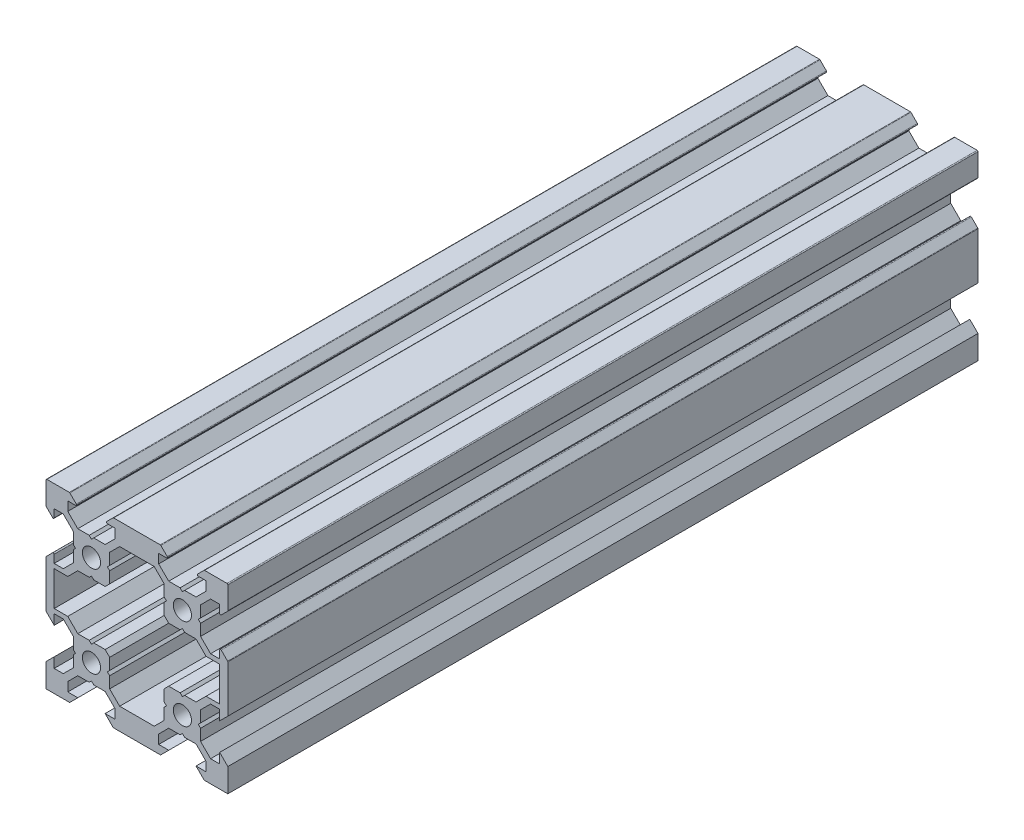
SolidWorks part; units mm, degrees
ref_plane "Front Plane" through (0, 0, 0) normal (0, 0, 1) x (1, 0, 0)
ref_plane "Top Plane" through (0, 0, 0) normal (0, 1, 0) x (1, 0, 0)
ref_plane "Right Plane" through (0, 0, 0) normal (1, 0, 0) x (0, 0, -1)
sketch "Sketch2" plane through (0, 0, 0) normal (0, 0, 1) x (1, 0, 0)
  line L160 (-6.4559, 12.7994) -> (-4.2559, 14.9994)
  line L161 (-4.2559, 14.9994) -> (3.3441, 14.9994)
  line L162 (3.3441, 14.9994) -> (5.5441, 12.7994)
  line L163 (5.5441, 12.7994) -> (5.5441, 10.2894)
  line L164 (5.5441, 10.2894) -> (6.0441, 9.7894)
  line L165 (6.0441, 9.7894) -> (5.5441, 9.2894)
  line L166 (5.5441, 9.2894) -> (5.5441, 6.7793)
  line L167 (5.5441, 6.7793) -> (6.5341, 5.7894)
  line L168 (6.5341, 5.7894) -> (9.0441, 5.7894)
  line L169 (9.0441, 5.7894) -> (9.5441, 6.2894)
  line L170 (9.5441, 6.2894) -> (10.0441, 5.7894)
  line L171 (10.0441, 5.7894) -> (12.5542, 5.7894)
  line L172 (12.5542, 5.7894) -> (14.7542, 3.5894)
  line L173 (14.7542, 3.5894) -> (17.7441, 3.5894)
  line L174 (17.7441, 3.5894) -> (17.7441, -4.0106)
  line L175 (17.7441, -4.0106) -> (14.7542, -4.0106)
  line L176 (14.7542, -4.0106) -> (12.5542, -6.2106)
  line L177 (12.5542, -6.2106) -> (10.0441, -6.2106)
  line L178 (9.5441, -6.7106) -> (10.0441, -6.2106)
  line L179 (9.0441, -6.2106) -> (9.5441, -6.7106)
  line L180 (9.0441, -6.2106) -> (6.5341, -6.2106)
  line L181 (6.5341, -6.2106) -> (5.5441, -7.2006)
  line L182 (5.5441, -7.2006) -> (5.5441, -9.7106)
  line L183 (6.0441, -10.2106) -> (5.5441, -9.7106)
  line L184 (5.5441, -10.7106) -> (6.0441, -10.2106)
  line L185 (5.5441, -10.7106) -> (5.5441, -13.2207)
  line L186 (5.5441, -13.2207) -> (3.3441, -15.4207)
  line L187 (3.3441, -15.4207) -> (-4.2559, -15.4207)
  line L188 (-4.2559, -15.4207) -> (-6.4559, -13.2207)
  line L189 (-6.4559, -13.2207) -> (-6.4559, -10.7106)
  line L190 (-6.9559, -10.2106) -> (-6.4559, -10.7106)
  line L191 (-6.4559, -9.7106) -> (-6.9559, -10.2106)
  line L192 (-6.4559, -9.7106) -> (-6.4559, -7.2006)
  line L193 (-6.4559, -7.2006) -> (-7.4458, -6.2106)
  line L194 (-7.4458, -6.2106) -> (-9.9559, -6.2106)
  line L195 (-10.4559, -6.7106) -> (-9.9559, -6.2106)
  line L196 (-10.9559, -6.2106) -> (-10.4559, -6.7106)
  line L197 (-10.9559, -6.2106) -> (-13.4659, -6.2106)
  line L198 (-13.4659, -6.2106) -> (-15.6659, -4.0106)
  line L199 (-15.6659, -4.0106) -> (-18.6559, -4.0106)
  line L200 (-18.6559, -4.0106) -> (-18.6559, 3.5894)
  line L201 (-18.6559, 3.5894) -> (-15.6659, 3.5894)
  line L202 (-15.6659, 3.5894) -> (-13.4659, 5.7894)
  line L203 (-13.4659, 5.7894) -> (-10.9559, 5.7894)
  line L204 (-10.9559, 5.7894) -> (-10.4559, 6.2894)
  line L205 (-10.4559, 6.2894) -> (-9.9559, 5.7894)
  line L206 (-9.9559, 5.7894) -> (-7.4458, 5.7894)
  line L207 (-7.4458, 5.7894) -> (-6.4559, 6.7793)
  line L208 (-6.4559, 9.2894) -> (-6.9559, 9.7894)
  line L209 (-6.9559, 9.7894) -> (-6.4559, 10.2894)
  line L210 (-6.4559, 6.7793) -> (-6.4559, 9.2894)
  line L211 (-6.4559, 10.2894) -> (-6.4559, 12.7994)
  line L212 (-5.2458, -16.4106) -> (-5.2458, -18.4106)
  line L213 (-5.2458, -18.4106) -> (-7.4559, -18.4106)
  line L214 (-7.4559, -18.4106) -> (-5.6559, -20.2106)
  line L215 (-5.6559, -20.2106) -> (4.7441, -20.2106)
  line L216 (4.7441, -20.2106) -> (6.5441, -18.4106)
  line L217 (6.5441, -18.4106) -> (4.3341, -18.4106)
  line L218 (4.3341, -18.4106) -> (4.3341, -16.4106)
  line L219 (4.3341, -16.4106) -> (6.5341, -14.2106)
  line L220 (6.5341, -14.2106) -> (9.0441, -14.2106)
  line L221 (9.0441, -14.2106) -> (9.5441, -13.7106)
  line L222 (9.5441, -13.7106) -> (10.0441, -14.2106)
  line L223 (10.0441, -14.2106) -> (12.5542, -14.2106)
  line L224 (12.5542, -14.2106) -> (14.7542, -16.4106)
  line L225 (14.7542, -16.4106) -> (14.7542, -18.4106)
  line L226 (14.7542, -18.4106) -> (12.5441, -18.4106)
  line L227 (12.5441, -18.4106) -> (14.3441, -20.2106)
  line L228 (14.3441, -20.2106) -> (19.5441, -20.2106)
  line L229 (19.5441, -20.2106) -> (19.5441, -15.0106)
  line L230 (19.5441, -15.0106) -> (17.7441, -13.2106)
  line L231 (17.7441, -13.2106) -> (17.7441, -15.4207)
  line L232 (17.7441, -15.4207) -> (15.7441, -15.4207)
  line L233 (15.7441, -15.4207) -> (13.5441, -13.2207)
  line L234 (13.5441, -13.2207) -> (13.5441, -10.7106)
  line L235 (13.5441, -10.7106) -> (13.0441, -10.2106)
  line L236 (13.0441, -10.2106) -> (13.5441, -9.7106)
  line L237 (13.5441, -9.7106) -> (13.5441, -7.2006)
  line L238 (13.5441, -7.2006) -> (15.7441, -5.0006)
  line L239 (15.7441, -5.0006) -> (17.7441, -5.0006)
  line L240 (17.7441, -5.0006) -> (17.7441, -7.2106)
  line L241 (17.7441, -7.2106) -> (19.5441, -5.4106)
  line L242 (19.5441, -5.4106) -> (19.5441, 4.9066)
  line L243 (19.4856, 5.048) -> (18.0856, 6.448)
  line L244 (17.7441, 6.3066) -> (17.7441, 4.5793)
  line L245 (17.7441, 4.5793) -> (15.7441, 4.5793)
  line L246 (15.7441, 4.5793) -> (13.5441, 6.7793)
  line L247 (13.5441, 6.7793) -> (13.5441, 9.2894)
  line L248 (13.5441, 9.2894) -> (13.0441, 9.7894)
  line L249 (13.0441, 9.7894) -> (13.5441, 10.2894)
  line L250 (13.5441, 10.2894) -> (13.5441, 12.7994)
  line L251 (13.5441, 12.7994) -> (15.7441, 14.9994)
  line L252 (15.7441, 14.9994) -> (17.7441, 14.9994)
  line L253 (17.7441, 14.9994) -> (17.7441, 13.2722)
  line L254 (18.0856, 13.1308) -> (19.4856, 14.5308)
  line L255 (19.5441, 14.6722) -> (19.5441, 19.5894)
  line L256 (19.3441, 19.7894) -> (14.427, 19.7894)
  line L257 (14.2856, 19.7308) -> (12.8856, 18.3308)
  line L258 (13.027, 17.9894) -> (14.7542, 17.9894)
  line L259 (14.7542, 17.9894) -> (14.7542, 15.9894)
  line L260 (14.7542, 15.9894) -> (12.5542, 13.7894)
  line L261 (12.5542, 13.7894) -> (10.0441, 13.7894)
  line L262 (10.0441, 13.7894) -> (9.5441, 13.2894)
  line L263 (9.5441, 13.2894) -> (9.0441, 13.7894)
  line L264 (9.0441, 13.7894) -> (6.5341, 13.7894)
  line L265 (6.5341, 13.7894) -> (4.3341, 15.9894)
  line L266 (4.3341, 15.9894) -> (4.3341, 17.9894)
  line L267 (4.3341, 17.9894) -> (6.0613, 17.9894)
  line L268 (6.2027, 18.3308) -> (4.8027, 19.7308)
  line L269 (4.6613, 19.7894) -> (-5.573, 19.7894)
  line L270 (-5.7144, 19.7308) -> (-7.1144, 18.3308)
  line L271 (-6.973, 17.9894) -> (-5.2458, 17.9894)
  line L272 (-5.2458, 17.9894) -> (-5.2458, 15.9894)
  line L273 (-5.2458, 15.9894) -> (-7.4458, 13.7894)
  line L274 (-7.4458, 13.7894) -> (-9.9559, 13.7894)
  line L275 (-9.9559, 13.7894) -> (-10.4559, 13.2894)
  line L276 (-10.4559, 13.2894) -> (-10.9559, 13.7894)
  line L277 (-10.9559, 13.7894) -> (-13.4659, 13.7894)
  line L278 (-13.4659, 13.7894) -> (-15.6659, 15.9894)
  line L279 (-15.6659, 15.9894) -> (-15.6659, 17.9894)
  line L280 (-15.6659, 17.9894) -> (-13.9387, 17.9894)
  line L281 (-13.7973, 18.3308) -> (-15.1973, 19.7308)
  line L282 (-15.3387, 19.7894) -> (-20.2559, 19.7894)
  line L283 (-20.4559, 19.5894) -> (-20.4559, 14.6722)
  line L284 (-20.3973, 14.5308) -> (-18.9973, 13.1308)
  line L285 (-18.6559, 13.2722) -> (-18.6559, 14.9994)
  line L286 (-18.6559, 14.9994) -> (-16.6559, 14.9994)
  line L287 (-16.6559, 14.9994) -> (-14.4559, 12.7994)
  line L288 (-14.4559, 12.7994) -> (-14.4559, 10.2894)
  line L289 (-14.4559, 10.2894) -> (-13.9559, 9.7894)
  line L290 (-13.9559, 9.7894) -> (-14.4559, 9.2894)
  line L291 (-14.4559, 9.2894) -> (-14.4559, 6.7793)
  line L292 (-14.4559, 6.7793) -> (-16.6559, 4.5793)
  line L293 (-16.6559, 4.5793) -> (-18.6559, 4.5793)
  line L294 (-18.6559, 4.5793) -> (-18.6559, 6.3066)
  line L295 (-18.9973, 6.448) -> (-20.3973, 5.048)
  line L296 (-20.4559, 4.9066) -> (-20.4559, -5.4106)
  line L297 (-20.4559, -5.4106) -> (-18.6559, -7.2106)
  line L298 (-18.6559, -7.2106) -> (-18.6559, -5.0006)
  line L299 (-18.6559, -5.0006) -> (-16.6559, -5.0006)
  line L300 (-16.6559, -5.0006) -> (-14.4559, -7.2006)
  line L301 (-14.4559, -7.2006) -> (-14.4559, -9.7106)
  line L302 (-14.4559, -9.7106) -> (-13.9559, -10.2106)
  line L303 (-13.9559, -10.2106) -> (-14.4559, -10.7106)
  line L304 (-14.4559, -10.7106) -> (-14.4559, -13.2207)
  line L305 (-14.4559, -13.2207) -> (-16.6559, -15.4207)
  line L306 (-16.6559, -15.4207) -> (-18.6559, -15.4207)
  line L307 (-18.6559, -15.4207) -> (-18.6559, -13.2106)
  line L308 (-18.6559, -13.2106) -> (-20.4559, -15.0106)
  line L309 (-20.4559, -15.0106) -> (-20.4559, -20.2106)
  line L310 (-20.4559, -20.2106) -> (-15.2559, -20.2106)
  line L311 (-15.2559, -20.2106) -> (-13.4559, -18.4106)
  line L312 (-13.4559, -18.4106) -> (-15.6659, -18.4106)
  line L313 (-15.6659, -18.4106) -> (-15.6659, -16.4106)
  line L314 (-15.6659, -16.4106) -> (-13.4659, -14.2106)
  line L315 (-13.4659, -14.2106) -> (-10.9559, -14.2106)
  line L316 (-10.9559, -14.2106) -> (-10.4559, -13.7106)
  line L317 (-10.4559, -13.7106) -> (-9.9559, -14.2106)
  line L318 (-9.9559, -14.2106) -> (-7.4458, -14.2106)
  line L319 (-7.4458, -14.2106) -> (-5.2458, -16.4106)
  line L320 (-13.9559, 9.7894) -> (-6.9559, 9.7894) construction
  line L321 (6.0441, 9.7894) -> (13.0441, 9.7894) construction
  line L322 (-13.9559, -10.2106) -> (-6.9559, -10.2106) construction
  line L323 (6.0441, -10.2106) -> (13.0441, -10.2106) construction
  arc A22 (19.5441, 4.9066) -> (19.4856, 5.048) centre (19.3441, 4.9066) ccw
  arc A23 (18.0856, 6.448) -> (17.7441, 6.3066) centre (17.9441, 6.3066) ccw
  arc A24 (17.7441, 13.2722) -> (18.0856, 13.1308) centre (17.9441, 13.2722) ccw
  arc A25 (19.4856, 14.5308) -> (19.5441, 14.6722) centre (19.3441, 14.6722) ccw
  arc A26 (19.5441, 19.5894) -> (19.3441, 19.7894) centre (19.3441, 19.5894) ccw
  arc A27 (14.427, 19.7894) -> (14.2856, 19.7308) centre (14.427, 19.5894) ccw
  arc A28 (12.8856, 18.3308) -> (13.027, 17.9894) centre (13.027, 18.1894) ccw
  arc A29 (6.0613, 17.9894) -> (6.2027, 18.3308) centre (6.0613, 18.1894) ccw
  arc A30 (4.8027, 19.7308) -> (4.6613, 19.7894) centre (4.6613, 19.5894) ccw
  arc A31 (-5.573, 19.7894) -> (-5.7144, 19.7308) centre (-5.573, 19.5894) ccw
  arc A32 (-7.1144, 18.3308) -> (-6.973, 17.9894) centre (-6.973, 18.1894) ccw
  arc A33 (-13.9387, 17.9894) -> (-13.7973, 18.3308) centre (-13.9387, 18.1894) ccw
  arc A34 (-15.1973, 19.7308) -> (-15.3387, 19.7894) centre (-15.3387, 19.5894) ccw
  arc A35 (-20.2559, 19.7894) -> (-20.4559, 19.5894) centre (-20.2559, 19.5894) ccw
  arc A36 (-20.4559, 14.6722) -> (-20.3973, 14.5308) centre (-20.2559, 14.6722) ccw
  arc A37 (-18.9973, 13.1308) -> (-18.6559, 13.2722) centre (-18.8559, 13.2722) ccw
  arc A38 (-18.6559, 6.3066) -> (-18.9973, 6.448) centre (-18.8559, 6.3066) ccw
  arc A39 (-20.3973, 5.048) -> (-20.4559, 4.9066) centre (-20.2559, 4.9066) ccw
  circle A40 centre (-10.4559, 9.7894) radius 2
  circle A41 centre (9.5441, 9.7894) radius 2
  circle A42 centre (-10.4559, -10.2106) radius 2
  circle A43 centre (9.5441, -10.2106) radius 2
  dimension "D1" = 4
extrude "Boss-Extrude1" add sketch "Sketch2" against normal blind 165
